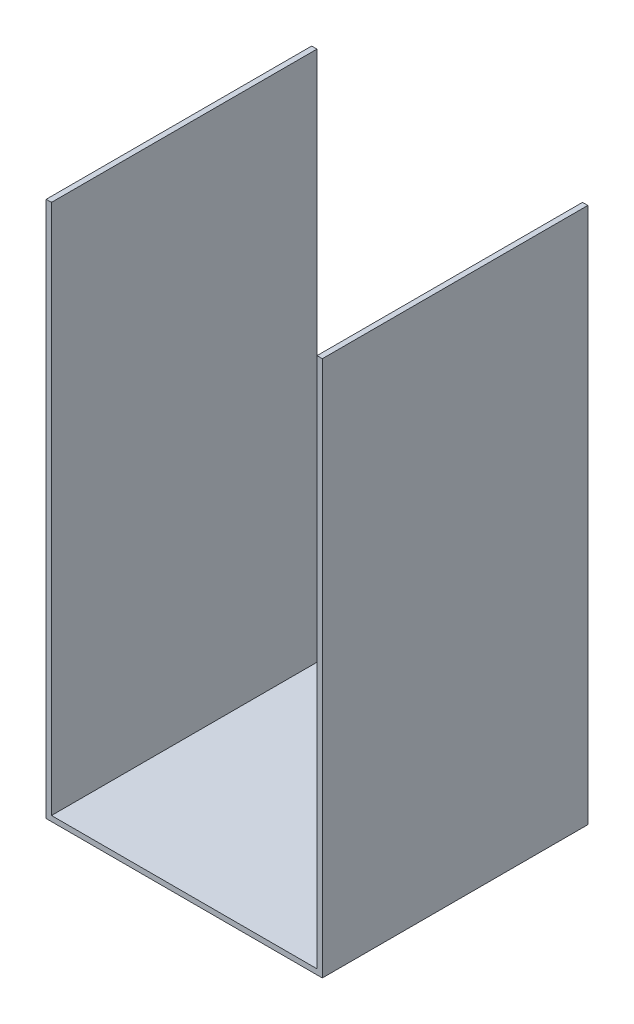
SolidWorks part; units mm, degrees
ref_plane "Front Plane" through (0, 0, 0) normal (0, 0, 1) x (1, 0, 0)
ref_plane "Top Plane" through (0, 0, 0) normal (0, 1, 0) x (1, 0, 0)
ref_plane "Right Plane" through (0, 0, 0) normal (1, 0, 0) x (0, 0, -1)
sketch "Sketch2" plane through (0, 0, 0) normal (0, 0, 1) x (1, 0, 0)
  line L0 (0, 0) -> (0, -20000)
  line L1 (0, -20000) -> (10000, -20000)
  line L2 (10000, -20000) -> (10000, 0)
  line L3 (-200, 0) -> (-200, -20200)
  line L4 (-200, -20200) -> (10200, -20200)
  line L5 (10200, -20200) -> (10200, 0)
  line L6 (-200, 0) -> (0, 0)
  line L7 (10000, 0) -> (10200, 0)
extrude "Boss-Extrude1" add sketch "Sketch2" against normal blind 10000
